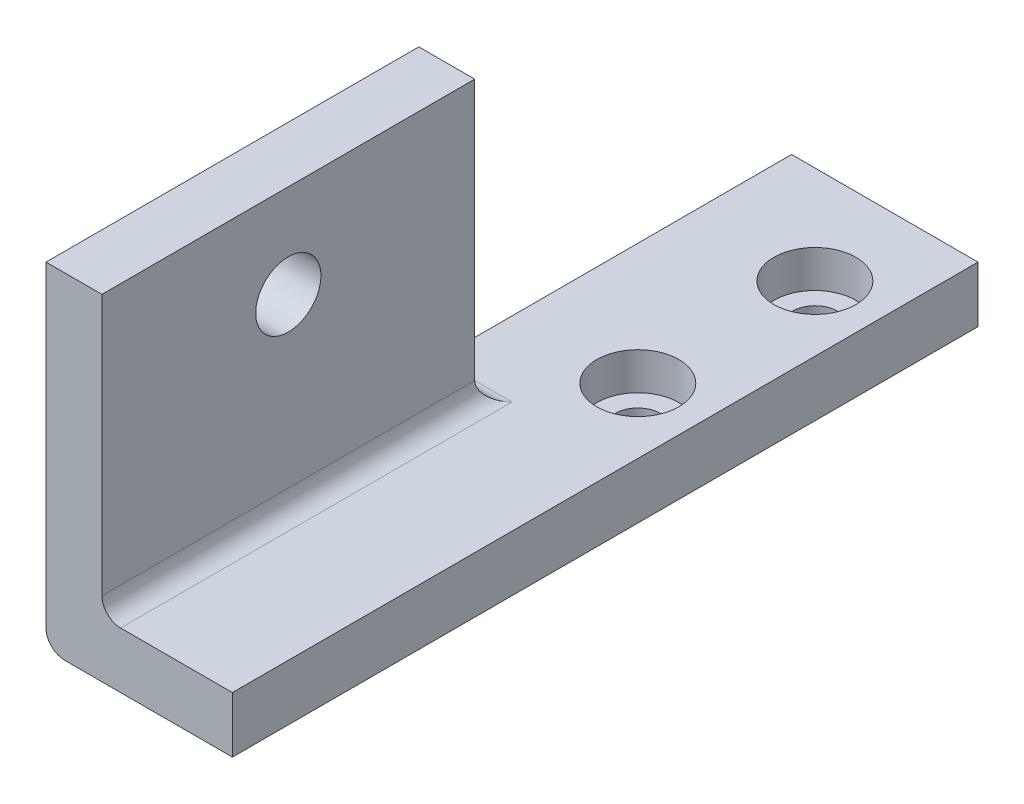
SolidWorks part; units mm, degrees
ref_plane "Front Plane" through (0, 0, 0) normal (0, 0, 1) x (1, 0, 0)
ref_plane "Top Plane" through (0, 0, 0) normal (0, 1, 0) x (1, 0, 0)
ref_plane "Right Plane" through (0, 0, 0) normal (1, 0, 0) x (0, 0, -1)
sketch "Sketch1" plane through (0, 0, 0) normal (0, 1, 0) x (1, 0, 0)
  line L0 (6.5, 5.25) -> (6.5, 14.75) construction
  line L1 (0, 0) -> (10, 0)
  line L2 (0, 0) -> (0, 20)
  line L3 (0, 20) -> (10, 20)
  line L4 (10, 0) -> (10, 20)
  circle A0 centre (6.5, 5.25) radius 1.175
  circle A1 centre (6.5, 14.75) radius 1.175
  point P9 (6.5, 10)
  point P10 (10, 10)
  dimension "D3" = 9.5
  dimension "D4" = 2.35
  dimension "D5" = 2.35
  dimension "D6" = 6.5
  dimension "D1" = 20
  dimension "D2" = 10
extrude "Boss-Extrude1" add sketch "Sketch1" along normal blind 3
sketch "Sketch2" plane through (0, 3, 0) normal (0, 1, 0) x (1, 0, 0)
  point P0 (6.5, 14.75)
  point P1 (6.5, 5.25)
hole_wizard "CBORE for M2 SHCS1" positions "Sketch2" profile "Sketch3" counterbore size "M2" standard "ANSI Metric" end condition through all
sketch "Sketch3" plane through (6.5, 3, -14.75) normal (1, 0, 0) x (0, 0, 1)
  line L0 (0, 0) -> (0, 3)
  line L1 (0, 3) -> (1.2, 3)
  line L3 (1.2, 3) -> (1.2, 2)
  line L4 (1.2, 2) -> (2.2, 2)
  line L5 (2.2, 2) -> (2.2, 0)
  line L7 (2.2, 0) -> (0, 0)
  line L11 (0, -6.35) -> (0, 107.95) construction
  dimension "Thru Hole Dia." = 2.4
  dimension "Thru Hole Depth" = 3
  dimension "C'Bore Dia." = 4.4
  dimension "C'Bore Depth" = 2
sketch "Sketch6" plane through (0, 0, 0) normal (0, 0, -1) x (-1, 0, 0)
  line L1 (0, 0) -> (-10, 0)
  line L2 (0, 0) -> (0, 3)
  line L3 (0, 3) -> (-10, 3)
  line L4 (-10, 0) -> (-10, 3)
  line L5 (-10, 3) -> (0, 3) construction
  line L6 (-10, 3) -> (-10, 0) construction
  dimension "D1" = 0
extrude "Boss-Extrude2" add sketch "Sketch6" against normal blind 20
sketch "Sketch8" plane through (0, 3, 0) normal (0, 1, 0) x (1, 0, 0)
  line L2 (0, -20) -> (3, -20)
  line L3 (0, -20) -> (0, 0)
  line L4 (0, 0) -> (3, 0)
  line L5 (3, -20) -> (3, 0)
  dimension "D1" = 3
  dimension "D2" = 20
extrude "Boss-Extrude3" add sketch "Sketch8" along normal blind 15
sketch "Sketch9" plane through (3, 0, 0) normal (1, 0, 0) x (0, 0, -1)
  line L1 (20, 3) -> (-20, 3) construction
  line L2 (-20, 18) -> (-20, 3) construction
  circle A0 centre (-10, 13) radius 1.75
  dimension "D1" = 10
  dimension "D2" = 10
  dimension "D3" = 3.5
extrude "Cut-Extrude1" cut sketch "Sketch9" against normal through all
fillet "Fillet1" radius 1 2 edges at (1.5, 3, 0) (3, 3, 10)
fillet "Fillet2" radius 1 1 edges at (0, 0, 0)
